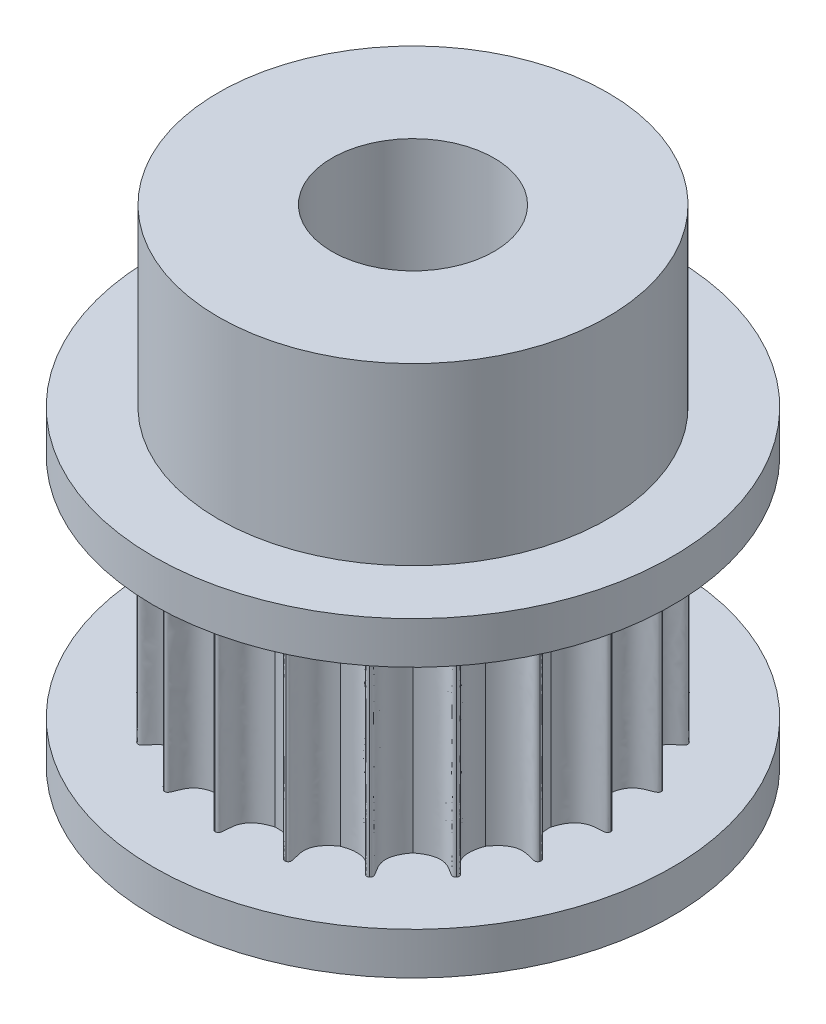
SolidWorks part; units mm, degrees
ref_plane "Front Plane" through (0, 0, 0) normal (0, 0, 1) x (1, 0, 0)
ref_plane "Top Plane" through (0, 0, 0) normal (0, 1, 0) x (1, 0, 0)
ref_plane "Right Plane" through (0, 0, 0) normal (1, 0, 0) x (0, 0, -1)
sketch "Sketch1" plane through (0, 0, 0) normal (0, 1, 0) x (1, 0, 0)
  circle A0 centre (0, 0) radius 8
  dimension "D1" = 16
extrude "Boss-Extrude1" add sketch "Sketch1" along normal blind 1.3
sketch "Sketch4" plane through (0, 1.3, 0) normal (0, 1, 0) x (1, 0, 0)
  circle A0 centre (0, 0) radius 5.0995
extrude "Boss-Extrude3" add sketch "Sketch4" along normal blind 7
sketch "Sketch2" plane through (0, 1.3, 0) normal (0, 1, 0) x (1, 0, 0)
  line L0 (0, 6.1) -> (0, 5.1) construction
  line L1 (-1, 5.1) -> (1, 5.1) construction
  line L2 (-1, 5.1) -> (-1, 5.001) construction
  line L3 (-1, 5.001) -> (1, 5.001) construction
  line L4 (1, 5.001) -> (1, 5.1) construction
  line L5 (1, 5.001) -> (-1, 5.001)
  circle A0 centre (0, 0) radius 5.1 construction
  circle A1 centre (0, 0) radius 6.1 construction
  spline S0 degree 3 poles (0, 6.1) (-0.3097, 6.0936) (0.2773, 5.2516) (-1, 5.001) knots 0 0 0 0 1 1 1 1
  spline S1 degree 3 poles (0, 6.1) (0.3097, 6.0936) (-0.2773, 5.2516) (1, 5.001) knots 0 0 0 0 1 1 1 1
  point P9 (0, 5.1)
  dimension "D1" = 12.2
  dimension "D2" = 1
  dimension "D3" = 2
extrude "Boss-Extrude2" add sketch "Sketch2" along normal up to surface (7 mm away) up to face at (0, 8.3, 5.0995)
ref_axis "Axis1" through (0, 1.3, 0) along (0, -1, 0)
pattern_circular "CirPattern1" count 20 over 360 about axis through (0, 1.3, 0) along (0, -1, 0) of "Boss-Extrude2"
sketch "Sketch5" plane through (0, 8.3, 0) normal (0, 1, 0) x (1, 0, 0)
  circle A0 centre (0, 0) radius 8
  circle A1 centre (0, 0) radius 8 construction
extrude "Boss-Extrude4" add sketch "Sketch5" along normal blind 1.3
sketch "Sketch6" plane through (0, 9.6, 0) normal (0, 1, 0) x (1, 0, 0)
  circle A0 centre (0, 0) radius 6
  dimension "D1" = 12
extrude "Boss-Extrude5" add sketch "Sketch6" along normal blind 5.4
sketch "Sketch7" plane through (0, 15, 0) normal (0, 1, 0) x (1, 0, 0)
  circle A0 centre (0, 0) radius 2.5
  dimension "D1" = 5
extrude "Cut-Extrude1" cut sketch "Sketch7" against normal up to next
